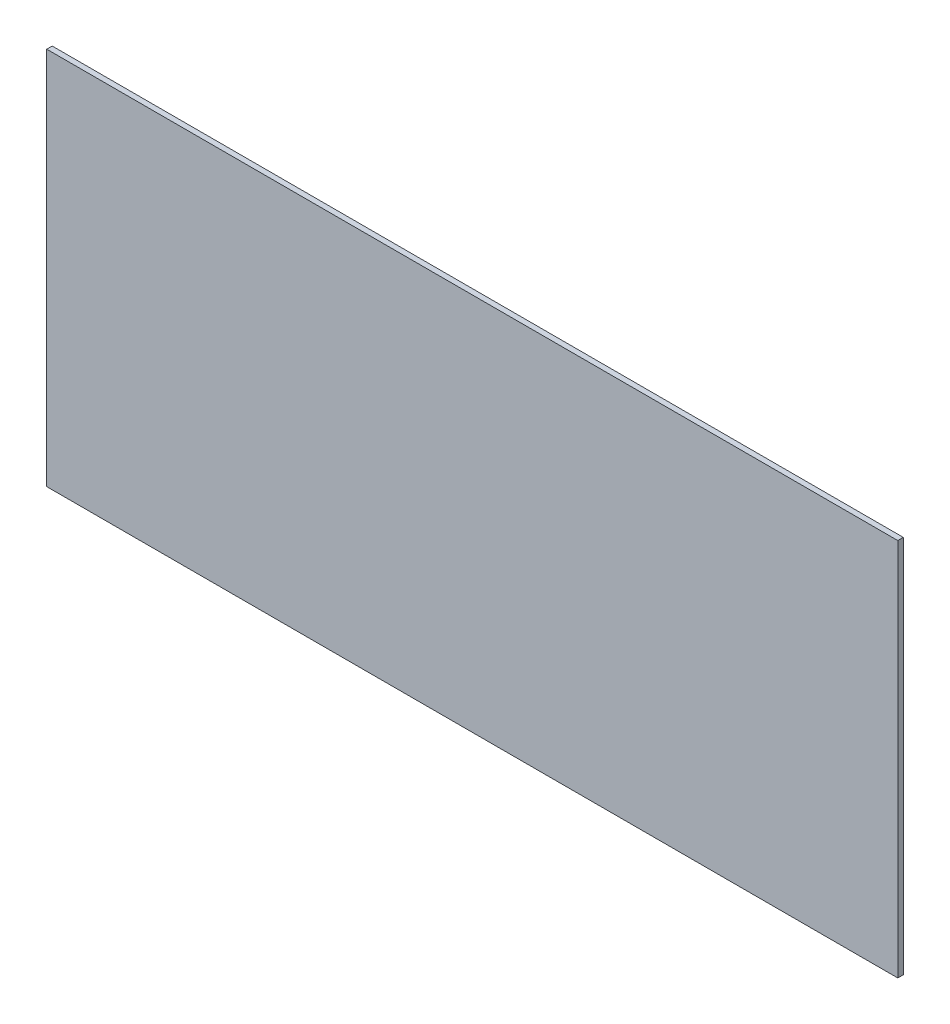
SolidWorks part; units mm, degrees
ref_plane "Front Plane" through (0, 0, 0) normal (0, 0, 1) x (1, 0, 0)
ref_plane "Top Plane" through (0, 0, 0) normal (0, 1, 0) x (1, 0, 0)
ref_plane "Right Plane" through (0, 0, 0) normal (1, 0, 0) x (0, 0, -1)
sketch "Sketch1" plane through (0, 0, 0) normal (0, 0, 1) x (1, 0, 0)
  line L1 (0, 0) -> (984.25, 0)
  line L2 (0, 0) -> (0, 438.15)
  line L3 (0, 438.15) -> (984.25, 438.15)
  line L4 (984.25, 0) -> (984.25, 438.15)
  dimension "D1" = 438.15
  dimension "D2" = 984.25
extrude "Boss-Extrude1" add sketch "Sketch1" along normal blind 6.35
